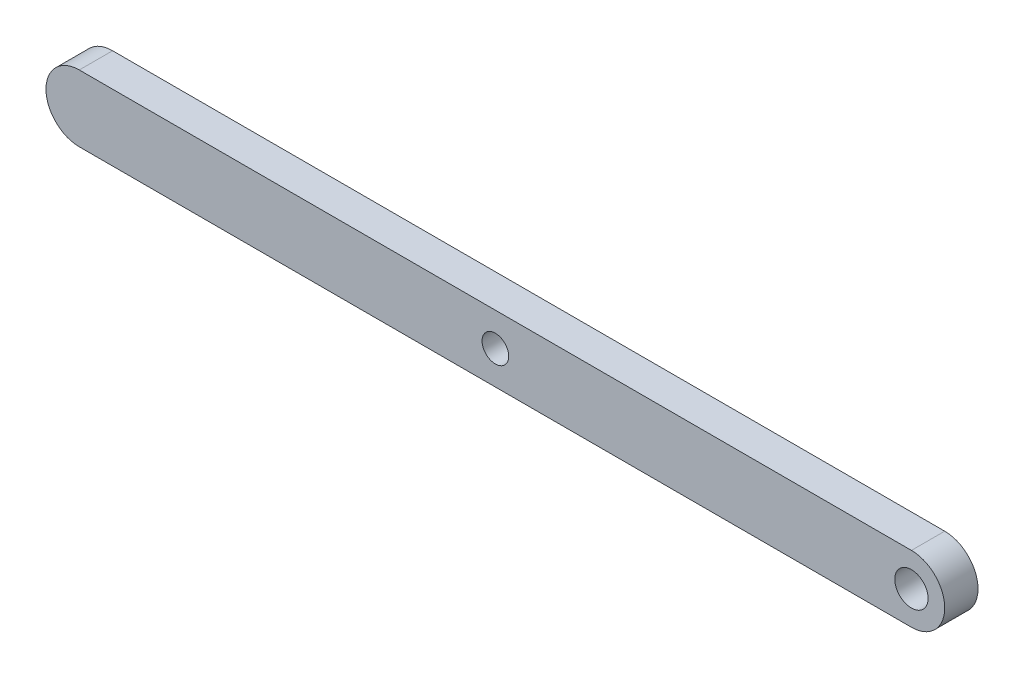
SolidWorks part; units mm, degrees
ref_plane "Front Plane" through (0, 0, 0) normal (0, 0, 1) x (1, 0, 0)
ref_plane "Top Plane" through (0, 0, 0) normal (0, 1, 0) x (1, 0, 0)
ref_plane "Right Plane" through (0, 0, 0) normal (1, 0, 0) x (0, 0, -1)
sketch "Sketch1" plane through (0, 0, 0) normal (0, 0, 1) x (1, 0, 0)
  line L1 (125, -10) -> (-125, -10)
  line L3 (125, 10) -> (-125, 10)
  line L5 (125, -10) -> (-125, 10) construction
  line L6 (125, 10) -> (-125, -10) construction
  arc A0 (-125, 10) -> (-125, -10) centre (-125, 0) ccw
  arc A1 (125, -10) -> (125, 10) centre (125, 0) ccw
  circle A2 centre (0, 0) radius 4
  circle A3 centre (125, 0) radius 5
  point P0 (0, 0)
  dimension "D3" = 10
  dimension "D4" = 8
  dimension "D6" = 10
  dimension "D7" = 10
  dimension "D1" = 20
  dimension "D2" = 250
  dimension "D5" = 20
extrude "Boss-Extrude1" add sketch "Sketch1" along normal blind 10
